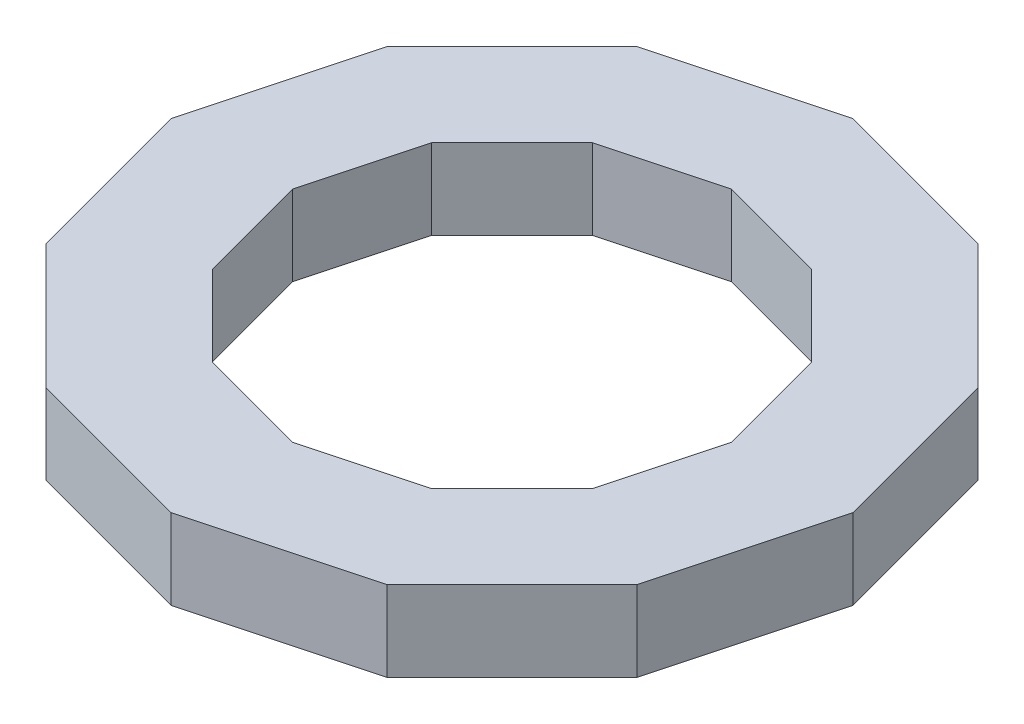
SolidWorks part; units mm, degrees
ref_plane "Front Plane" through (0, 0, 0) normal (0, 0, 1) x (1, 0, 0)
ref_plane "Top Plane" through (0, 0, 0) normal (0, 1, 0) x (1, 0, 0)
ref_plane "Right Plane" through (0, 0, 0) normal (1, 0, 0) x (0, 0, -1)
sketch "Sketch1" plane through (0, 0, 0) normal (0, 1, 0) x (1, 0, 0)
  line L0 (0, 0) -> (52.0383, 0) construction
  line L1 (52.0383, 0) -> (45.0665, 26.0191)
  line L2 (45.0665, 26.0191) -> (26.0191, 45.0665)
  line L3 (26.0191, 45.0665) -> (0, 52.0383)
  line L4 (0, 52.0383) -> (-26.0191, 45.0665)
  line L5 (-26.0191, 45.0665) -> (-45.0665, 26.0191)
  line L6 (-45.0665, 26.0191) -> (-52.0383, 0)
  line L7 (-52.0383, 0) -> (-45.0665, -26.0191)
  line L8 (-45.0665, -26.0191) -> (-26.0191, -45.0665)
  line L9 (-26.0191, -45.0665) -> (0, -52.0383)
  line L10 (0, -52.0383) -> (26.0191, -45.0665)
  line L11 (26.0191, -45.0665) -> (45.0665, -26.0191)
  line L12 (45.0665, -26.0191) -> (52.0383, 0)
  line L13 (80.9639, 0) -> (70.1168, 40.482)
  line L14 (70.1168, 40.482) -> (40.482, 70.1168)
  line L15 (40.482, 70.1168) -> (0, 80.9639)
  line L16 (0, 80.9639) -> (-40.482, 70.1168)
  line L17 (-40.482, 70.1168) -> (-70.1168, 40.482)
  line L18 (-70.1168, 40.482) -> (-80.9639, 0)
  line L19 (-80.9639, 0) -> (-70.1168, -40.482)
  line L20 (-70.1168, -40.482) -> (-40.482, -70.1168)
  line L21 (-40.482, -70.1168) -> (0, -80.9639)
  line L22 (0, -80.9639) -> (40.482, -70.1168)
  line L23 (40.482, -70.1168) -> (70.1168, -40.482)
  line L24 (70.1168, -40.482) -> (80.9639, 0)
  circle A0 centre (0, 0) radius 50.2651 construction
  circle A1 centre (0, 0) radius 78.2051 construction
  dimension "D1" = 27.94
  dimension "D2" = 41.91
extrude "Boss-Extrude1" add sketch "Sketch1" along normal blind 19.05
